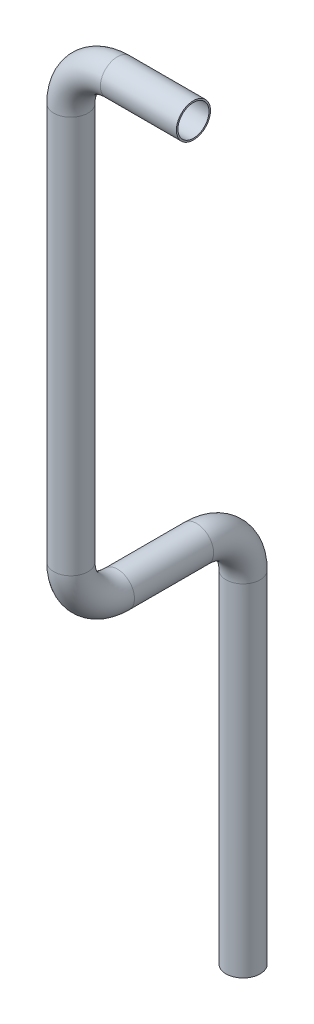
SolidWorks part; units mm, degrees
ref_plane "Plan de face" through (0, 0, 0) normal (0, 0, 1) x (1, 0, 0)
ref_plane "Plan de dessus" through (0, 0, 0) normal (0, 1, 0) x (1, 0, 0)
ref_plane "Plan de droite" through (0, 0, 0) normal (1, 0, 0) x (0, 0, -1)
sketch3d "Esquisse3D1"
  line L0 (0, 0, 0) -> (0, 110, 0)
  line L1 (0, 125, 15) -> (0, 125, 40.5)
  line L2 (0, 140, 55.5) -> (0, 268, 55.5)
  line L3 (15, 283, 55.5) -> (39.5, 283, 55.5)
  arc A0 (0, 110, 0) -> (0, 125, 15) centre (0, 110, 15) ccw
  arc A1 (0, 125, 40.5) -> (0, 140, 55.5) centre (0, 140, 40.5) ccw
  arc A2 (0, 268, 55.5) -> (15, 283, 55.5) centre (15, 268, 55.5) ccw
  point P8 (0, 125, 0)
  point P9 (15, 110, 15)
  point P12 (0, 125, 55.5)
  point P13 (-15, 140, 40.5)
  point P16 (0, 283, 55.5)
  point P17 (15, 268, 40.5)
  dimension "D1" = 15
sketch "Esquisse1" plane through (0, 0, 0) normal (0, 1, 0) x (1, 0, 0)
  circle A0 centre (0, 0) radius 5
  circle A1 centre (0, 0) radius 5.5
sweep "Balayage1" add profiles "Esquisse1" path "Esquisse3D1"
